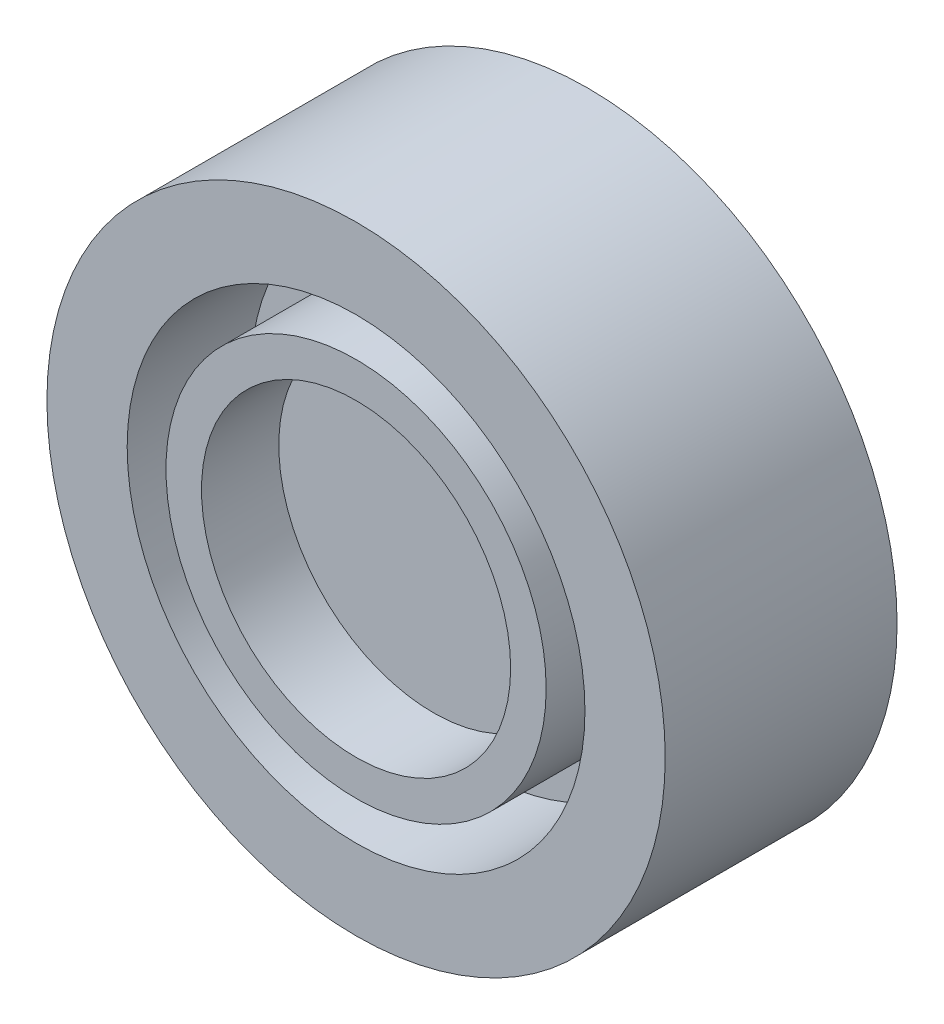
SolidWorks part; units mm, degrees
material "PE High Density"
ref_plane "Front" through (0, 0, 0) normal (0, 0, 1) x (1, 0, 0)
ref_plane "Top" through (0, 0, 0) normal (0, 1, 0) x (1, 0, 0)
ref_plane "Right" through (0, 0, 0) normal (1, 0, 0) x (0, 0, -1)
sketch "Sketch1" plane through (0, 0, 0) normal (0, 0, 1) x (1, 0, 0)
  circle A0 centre (0, 0) radius 20
extrude "Boss-Extrude1" add sketch "Sketch1" along normal blind 15
sketch "Sketch2" plane through (0, 0, 15) normal (0, 0, 1) x (1, 0, 0)
  circle A0 centre (0, 0) radius 10
extrude "Cut-Extrude2" cut sketch "Sketch2" against normal blind 5
sketch "Sketch4" plane through (0, 0, 15) normal (0, 0, 1) x (1, 0, 0)
  circle A0 centre (0, 0) radius 12.2982
  circle A1 centre (0, 0) radius 14.8079
extrude "Cut-Extrude3" cut sketch "Sketch4" against normal blind 8
